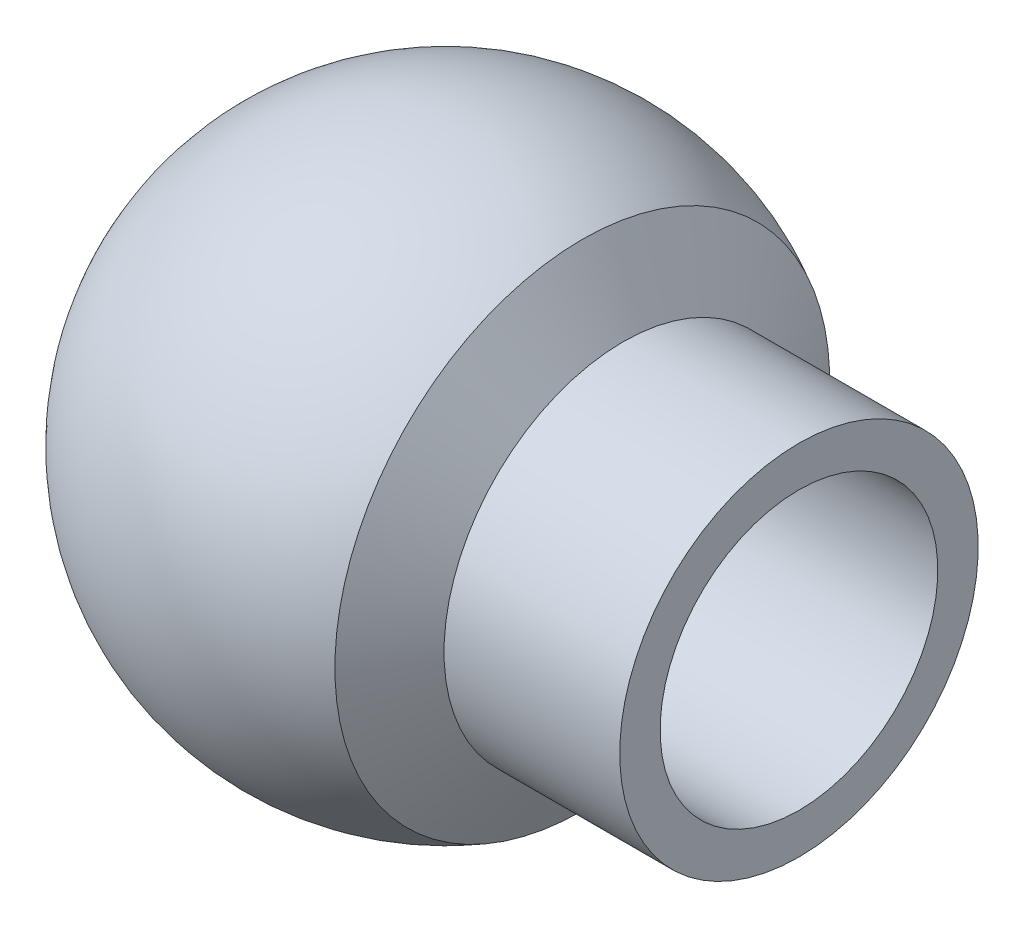
SolidWorks part; units mm, degrees
ref_plane "Front Plane" through (0, 0, 0) normal (0, 0, 1) x (1, 0, 0)
ref_plane "Top Plane" through (0, 0, 0) normal (0, 1, 0) x (1, 0, 0)
ref_plane "Right Plane" through (0, 0, 0) normal (1, 0, 0) x (0, 0, -1)
sketch "Sketch1" plane through (0, 0, 0) normal (0, 0, 1) x (1, 0, 0)
  line L0 (0, 4.005) -> (0, 2.005)
  line L2 (-20, -4.87) -> (-31.5, -4.87)
  line L3 (0, 4.005) -> (-8.7, 4.005)
  line L5 (0, 2.005) -> (-20, 2.005)
  line L7 (0, 2.005) -> (-115.5683, 2.005) construction
  line L8 (-20, 2.005) -> (-20, -4.87)
  line L11 (0, -4.87) -> (-115.5683, -4.87) construction
  line L13 (-10.7264, 7.3823) -> (-8.7, 4.005)
  line L19 (0, 4.005) -> (-115.5683, 4.005) construction
  arc A1 (-10.7264, 7.3823) -> (-31.5, -4.87) centre (-17.5, -4.87) ccw
  dimension "D3" = 28
  dimension "D2" = 8.875
  dimension "D6" = 2
  dimension "D8" = 3.3773
  dimension "D4" = 2
revolve "Revolve1" add sketch "Sketch1" angle 360 about L2
